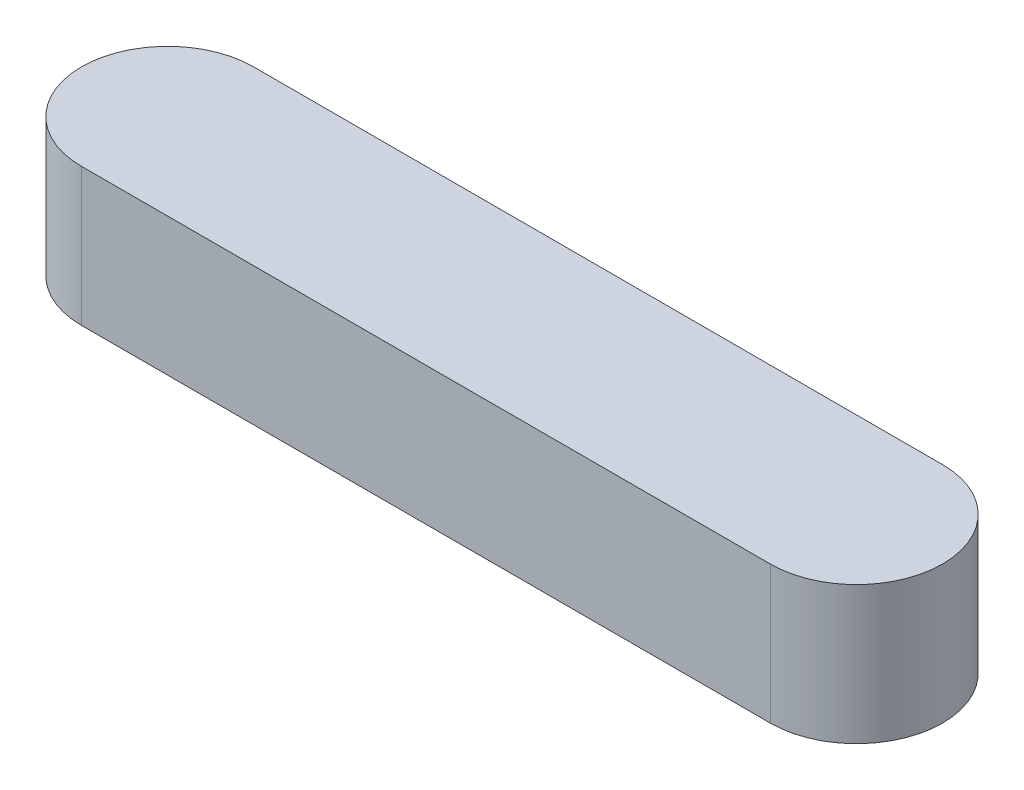
SolidWorks part; units mm, degrees
ref_plane "Спереди" through (0, 0, 0) normal (0, 0, 1) x (1, 0, 0)
ref_plane "Сверху" through (0, 0, 0) normal (0, 1, 0) x (1, 0, 0)
ref_plane "Справа" through (0, 0, 0) normal (1, 0, 0) x (0, 0, -1)
other "Configuration Table"
sketch "Эскиз1" plane through (0, 0, 0) normal (0, 1, 0) x (1, 0, 0)
  line L0 (-20, 0) -> (20, 0) construction
  line L1 (-20, 5) -> (20, 5)
  line L2 (-20, -5) -> (20, -5)
  arc A0 (-20, 5) -> (-20, -5) centre (-20, 0) ccw
  arc A1 (20, -5) -> (20, 5) centre (20, 0) ccw
  point P2 (0, 0)
  dimension "D1" = 50
  dimension "D2" = 5
extrude "Бобышка-Вытянуть1" add sketch "Эскиз1" along normal blind 8
